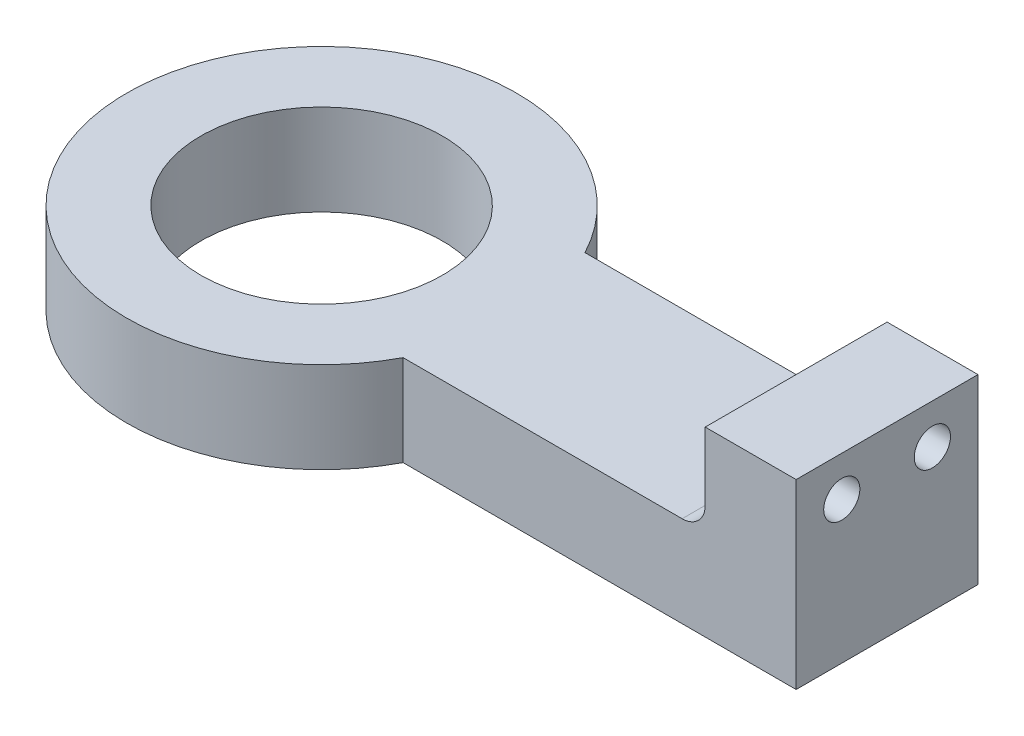
SolidWorks part; units mm, degrees
ref_plane "Front Plane" through (0, 0, 0) normal (0, 0, 1) x (1, 0, 0)
ref_plane "Top Plane" through (0, 0, 0) normal (0, 1, 0) x (1, 0, 0)
ref_plane "Right Plane" through (0, 0, 0) normal (1, 0, 0) x (0, 0, -1)
sketch "Sketch1" plane through (0, 0, 0) normal (0, 1, 0) x (1, 0, 0)
  line L1 (37.9228, 20) -> (124.3728, 20)
  line L2 (37.9228, 20) -> (37.9228, -20)
  line L3 (37.9228, -20) -> (124.3728, -20)
  line L4 (124.3728, 20) -> (124.3728, -20)
  circle A0 centre (0, 0) radius 26.5621
  circle A2 centre (0, 0) radius 42.8735
  dimension "D1" = 53.1241
  dimension "D4" = 85.7471
  dimension "D2" = 86.45
  dimension "D3" = 40
extrude "Boss-Extrude2" add sketch "Sketch1" along normal blind 20 contours L2 A2 A0 | A2 L3 L4 L1 | L2 A2
sketch "Sketch2" plane through (0, 0, -20) normal (0, 0, -1) x (-1, 0, 0)
  line L1 (-124.3728, 20) -> (-104.3728, 20)
  line L2 (-124.3728, 20) -> (-124.3728, 40)
  line L3 (-124.3728, 40) -> (-104.3728, 40)
  line L4 (-104.3728, 20) -> (-104.3728, 40)
extrude "Boss-Extrude3" add sketch "Sketch2" against normal up to surface (40 mm away) up to face at (81.1478, 10, 20)
sketch "Sketch3" plane through (104.3728, 0, 0) normal (-1, 0, 0) x (0, 0, 1)
  line L0 (-20, 20) -> (-20, 40) construction
  line L1 (20, 40) -> (-20, 40) construction
  line L2 (20, 40) -> (20, 20) construction
  circle A0 centre (9.9619, 31.2218) radius 3.9774
  circle A1 centre (-9.9619, 31.2218) radius 3.9851
  point P10 (0, 0)
  point P11 (0, 0)
  point P12 (0, 0)
  point P13 (0, 0)
  point P14 (0, 0)
  dimension "D1" = 7.9547
  dimension "D2" = 7.9703
  dimension "D3" = 10.0381
  dimension "D4" = 8.7782
  dimension "D5" = 8.7782
  dimension "D6" = 10.0381
extrude "Cut-Extrude1" cut sketch "Sketch3" against normal through all
fillet "Fillet1" radius 5.08 1 edges at (104.3728, 20, 0)
